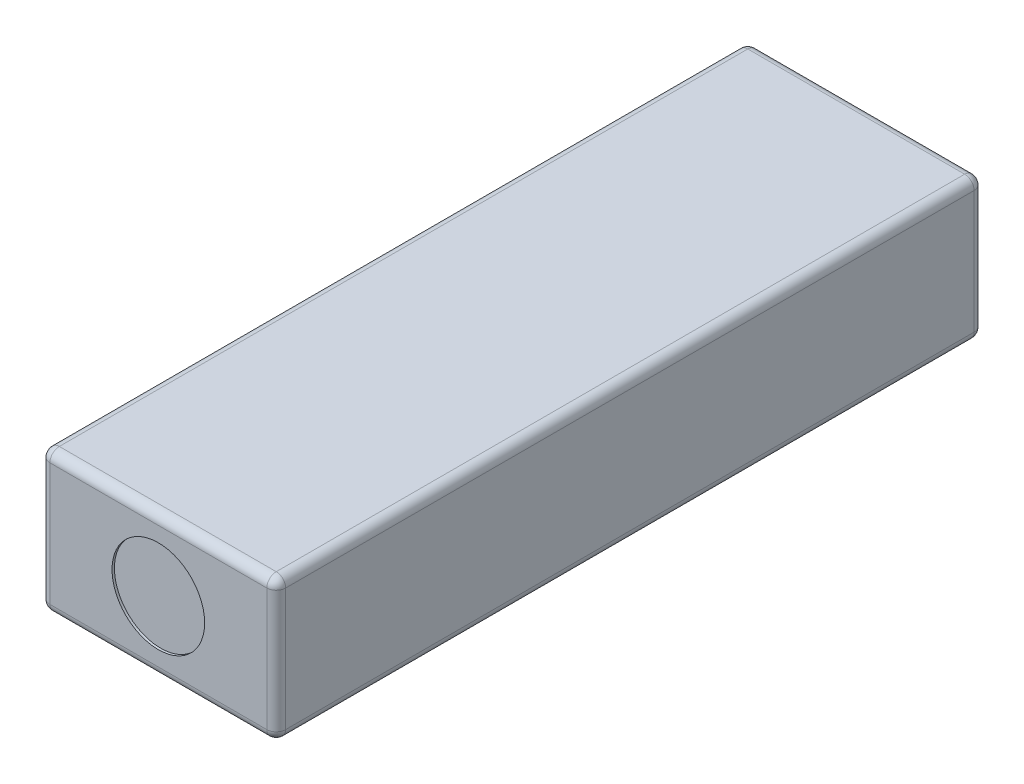
SolidWorks part; units mm, degrees
ref_plane "Front Plane" through (0, 0, 0) normal (0, 0, 1) x (1, 0, 0)
ref_plane "Top Plane" through (0, 0, 0) normal (0, 1, 0) x (1, 0, 0)
ref_plane "Right Plane" through (0, 0, 0) normal (1, 0, 0) x (0, 0, -1)
sketch "Sketch2" plane through (0, 0, 0) normal (0, 1, 0) x (1, 0, 0)
  line L1 (-25, 75) -> (25, 75)
  line L2 (-25, 75) -> (-25, -75)
  line L3 (-25, -75) -> (25, -75)
  line L4 (25, 75) -> (25, -75)
  line L5 (-25, 75) -> (25, -75) construction
  line L6 (-25, -75) -> (25, 75) construction
  point P0 (0, 0)
  dimension "D1" = 50
  dimension "D2" = 150
extrude "Boss-Extrude1" add sketch "Sketch2" along normal blind 30
fillet "Fillet1" radius 2 12 edges at (25, 0, 0) (25, 15, 75) (0, 0, 75) (25, 15, -75) (0, 0, -75) (0, 30, 75) (0, 30, -75) (25, 30, 0) (-25, 15, -75) (-25, 30, 0) (-25, 15, 75) (-25, 0, 0)
sketch "Sketch3" plane through (0, 0, 75) normal (0, 0, 1) x (1, 0, 0)
  circle A0 centre (0, 15) radius 9.8178
extrude "Cut-Extrude1" cut sketch "Sketch3" against normal blind 0.5
